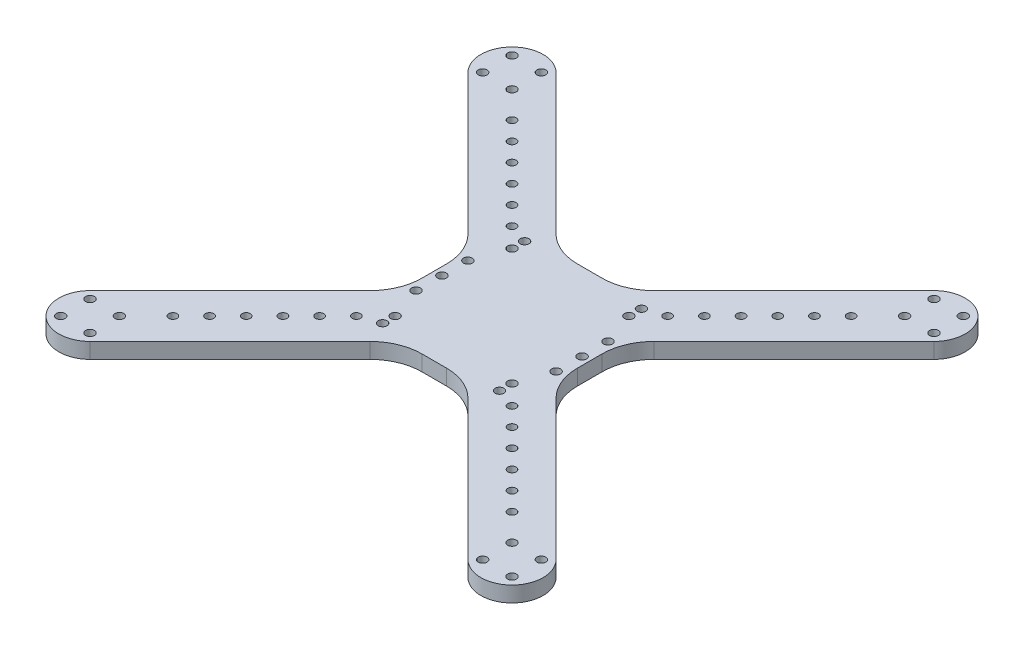
SolidWorks part; units mm, degrees
ref_plane "Front Plane" through (0, 0, 0) normal (0, 0, 1) x (1, 0, 0)
ref_plane "Top Plane" through (0, 0, 0) normal (0, 1, 0) x (1, 0, 0)
ref_plane "Right Plane" through (0, 0, 0) normal (1, 0, 0) x (0, 0, -1)
sketch "Sketch1" plane through (0, 0, 0) normal (0, 1, 0) x (1, 0, 0)
  line L0 (-81.3173, 81.3173) -> (81.3173, -81.3173) construction
  line L1 (-98.425, -98.425) -> (98.425, -98.425) construction
  line L2 (-98.425, -98.425) -> (-98.425, 98.425) construction
  line L3 (-98.425, 98.425) -> (98.425, 98.425) construction
  line L4 (98.425, -98.425) -> (98.425, 98.425) construction
  line L5 (-98.425, -98.425) -> (98.425, 98.425) construction
  line L6 (-98.425, 98.425) -> (98.425, -98.425) construction
  line L7 (-72.832, 89.8026) -> (-13.0294, 30)
  line L8 (-89.8026, 72.832) -> (-30, 13.0294)
  line L9 (0, 98.425) -> (0, -98.425) construction
  line L10 (81.3173, 81.3173) -> (-81.3173, -81.3173) construction
  line L11 (72.832, 89.8026) -> (13.0294, 30)
  line L12 (89.8026, 72.832) -> (30, 13.0294)
  line L13 (-30, -13.0294) -> (-89.8026, -72.832)
  line L14 (-13.0294, -30) -> (13.0294, -30)
  line L15 (-30, -13.0294) -> (-30, 13.0294)
  line L16 (-13.0294, 30) -> (13.0294, 30)
  line L17 (30, -13.0294) -> (30, 13.0294)
  line L18 (-30, -30) -> (30, 30) construction
  line L19 (-30, 30) -> (30, -30) construction
  line L20 (-13.0294, -30) -> (-72.832, -89.8026)
  line L21 (30, -13.0294) -> (89.8026, -72.832)
  line L22 (13.0294, -30) -> (72.832, -89.8026)
  arc A0 (-72.832, 89.8026) -> (-89.8026, 72.832) centre (-81.3173, 81.3173) ccw
  arc A1 (72.832, -89.8026) -> (89.8026, -72.832) centre (81.3173, -81.3173) ccw
  circle A2 centre (-81.3173, 81.3173) radius 8 construction
  circle A3 centre (81.3173, -81.3173) radius 8 construction
  circle A4 centre (-81.3173, -81.3173) radius 8 construction
  circle A5 centre (81.3173, 81.3173) radius 8 construction
  arc A6 (72.832, 89.8026) -> (89.8026, 72.832) centre (81.3173, 81.3173) cw
  arc A7 (-72.832, -89.8026) -> (-89.8026, -72.832) centre (-81.3173, -81.3173) cw
  point P0 (0, 0)
  point P8 (0, 0)
  point P23 (0, 0)
  point P29 (0, 0)
  point P42 (30, 0)
  dimension "D2" = 12
  dimension "D4" = 16
  dimension "D6" = 12
  dimension "D9" = 12
  dimension "D10" = 12
  dimension "D1" = 196.85
  dimension "D3" = 115
  dimension "D5" = 115
  dimension "D8" = 26.0589
  dimension "D11" = 30
  dimension "D12" = 30
extrude "Boss-Extrude1" add sketch "Sketch1" along normal blind 6
fillet "Fillet1" radius 20 8 edges at (-30, 3, -13.0294) (-30, 3, 13.0294) (-13.0294, 3, -30) (13.0294, 3, -30) (30, 3, 13.0294) (30, 3, -13.0294) (13.0294, 3, 30) (-13.0294, 3, 30)
ref_axis "Axis1" through (0, 6.3, 0) along (0, -1, 0)
ref_plane "Plane1" through (0, 0, 0) normal (-0.7071, 0, 0.7071) x (0, -1, 0)
sketch "Sketch2" plane through (0, 6, 0) normal (0, 1, 0) x (1, 0, 0)
  line L0 (0, 0) -> (-25, 0)
  line L1 (-25, 0) -> (-25, -25)
  line L2 (-25, -25) -> (0, -25)
  line L3 (0, -25) -> (0, 0)
  circle A1 centre (-22.525, -22.525) radius 1.7
  dimension "D4" = 3.4
  dimension "D1" = 25
  dimension "D2" = 22.525
  dimension "D3" = 22.525
extrude "Cut-Extrude1" cut sketch "Sketch2" against normal through all contours A1
pattern_circular "CirPattern1" count 4 over 360 about axis through (0, 0, 0) along (0, 1, 0) of "Cut-Extrude1"
sketch "Sketch3" plane through (0, 6, 0) normal (0, 1, 0) x (1, 0, 0)
  line L0 (0, 0) -> (-89.8026, -89.8026) construction
  circle A0 centre (-30, -30) radius 1.6
  arc A1 (-89.8026, -72.832) -> (-72.832, -89.8026) centre (-81.3173, -81.3173) ccw construction
  dimension "D1" = 3.2
  dimension "D2" = 30
extrude "Cut-Extrude2" cut sketch "Sketch3" against normal through all
pattern_linear "LPattern1" count 6 spacing 10 along (-0.7071, 0, 0.7071) of "Cut-Extrude2"
pattern_circular "CirPattern2" count 4 over 360 about axis through (0, 6.3, 0) along (0, -1, 0) of "LPattern1", "Cut-Extrude2"
sketch "Sketch4" plane through (0, 6, 0) normal (0, 1, 0) x (1, 0, 0)
  line L0 (-89.8026, -72.832) -> (-72.832, -89.8026) construction
  line L1 (-75.6604, -75.6604) -> (-86.9741, -86.9741) construction
  circle A0 centre (-81.3173, -81.3173) radius 8
  circle A1 centre (-86.9741, -86.9741) radius 1.7
  circle A2 centre (-86.9741, -75.6604) radius 1.7
  circle A3 centre (-75.6604, -75.6604) radius 1.7
  circle A4 centre (-75.6604, -86.9741) radius 1.7
  dimension "D1" = 16
  dimension "D2" = 3.4
extrude "Cut-Extrude3" cut sketch "Sketch4" against normal through all contours A0 A2 | A0 A2 | A0 A3 | A0 A3 | A0 A4 | A0 A4 | A0 A1 | A0 A1
pattern_circular "CirPattern3" count 4 over 360 about axis through (0, 0, 0) along (0, 1, 0) of "Cut-Extrude3"
sketch "Sketch5" plane through (0, 6, 0) normal (0, 1, 0) x (1, 0, 0)
  line L0 (-22.525, -22.525) -> (-22.525, 27.375) construction
  line L1 (0, 0) -> (-22.525, 0) construction
  line L2 (-22.525, 0) -> (-22.525, -27.35) construction
  circle A0 centre (-22.525, 27.375) radius 1.7
  circle A1 centre (-22.525, -27.35) radius 1.7
  dimension "D2" = 3.4
  dimension "D5" = 3.4
  dimension "D1" = 49.9
  dimension "D3" = 27.375
  dimension "D4" = 27.35
extrude "Cut-Extrude4" cut sketch "Sketch5" against normal through all contours A0 | A1
mirror "Mirror1" about plane through (0, 0, 0) normal (1, 0, 0) of "Cut-Extrude4"
sketch "Sketch6" plane through (0, 6, 0) normal (0, 1, 0) x (1, 0, 0)
  line L0 (-2.5668, 2.5668) -> (2.5668, -2.5668) construction
  line L1 (-89.8026, 72.832) -> (-72.832, 89.8026) construction
  circle A0 centre (-81.3173, 81.3173) radius 63.5
sketch "Sketch7" plane through (0, 6, 0) normal (0, 1, 0) x (1, 0, 0)
  line L0 (-30, 4.7452) -> (-30, -4.7452) construction
  line L1 (-27, 0) -> (0, 0) construction
  circle A0 centre (-27, 0) radius 1.7
  dimension "D1" = 3.4
  dimension "D2" = 3
extrude "Cut-Extrude5" cut sketch "Sketch7" against normal through all
pattern_linear "LPattern2" count 2 spacing 10 along (0, 0, 1) count 2 spacing 10 along (0, 0, -1) of "Cut-Extrude5"
mirror "Mirror2" about plane through (0, 0, 0) normal (1, 0, 0) of "LPattern2", "Cut-Extrude5"
